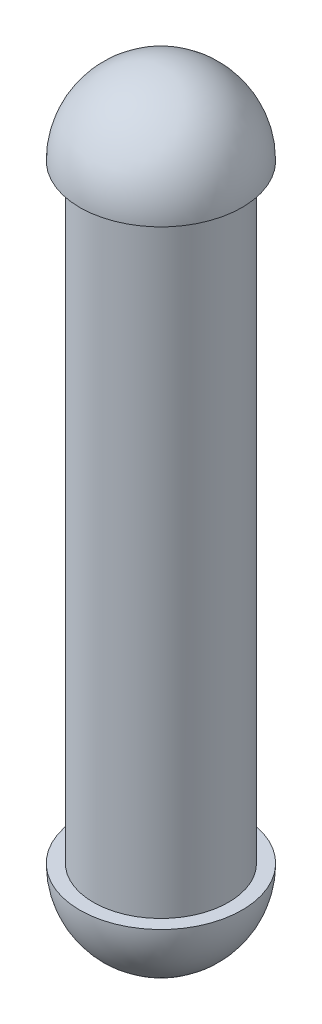
SolidWorks part; units mm, degrees
ref_plane "Front Plane" through (0, 0, 0) normal (0, 0, 1) x (1, 0, 0)
ref_plane "Top Plane" through (0, 0, 0) normal (0, 1, 0) x (1, 0, 0)
ref_plane "Right Plane" through (0, 0, 0) normal (1, 0, 0) x (0, 0, -1)
sketch "Sketch1" plane through (0, 0, 0) normal (0, 1, 0) x (1, 0, 0)
  circle A0 centre (0, 0) radius 1
  dimension "D1" = 2
extrude "Boss-Extrude1" add sketch "Sketch1" along normal mid plane 9
sketch "Sketch2" plane through (0, 4.5, 0) normal (0, 1, 0) x (1, 0, 0)
  line L0 (0, 1.2) -> (0, -1.2)
  arc A0 (0, 1.2) -> (0, -1.2) centre (0, 0) ccw
  circle A1 centre (0, 0) radius 1 construction
  dimension "D1" = 1.2
revolve "Revolve1" add sketch "Sketch2" angle 180 about L0
mirror "Mirror1" about plane through (0, 0, 0) normal (0, 1, 0) of "Revolve1"
